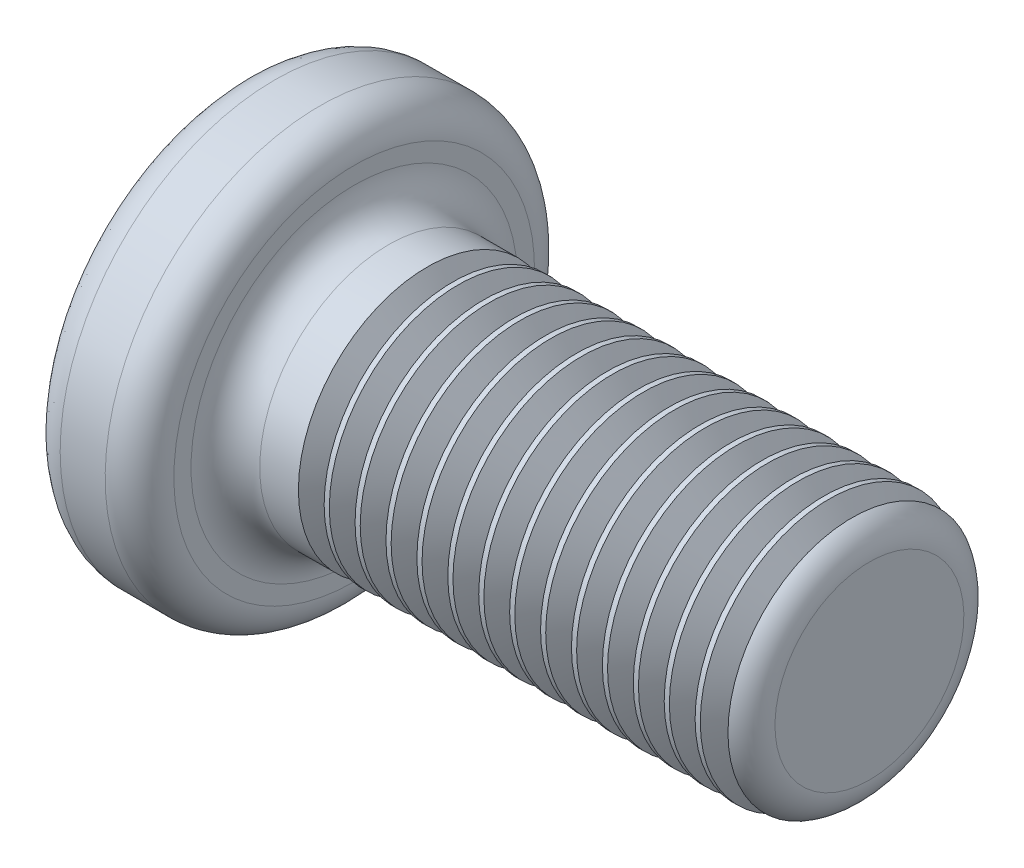
SolidWorks part; units mm, degrees
ref_plane "Front" through (0, 0, 0) normal (0, 0, 1) x (1, 0, 0)
ref_plane "Top" through (0, 0, 0) normal (0, 1, 0) x (1, 0, 0)
ref_plane "Right" through (0, 0, 0) normal (1, 0, 0) x (0, 0, -1)
sketch "Sketch1" plane through (0, 0, 0) normal (0, 0, 1) x (1, 0, 0)
  line L0 (-8.6356, 0) -> (3, 0) construction
  line L1 (8, 0) -> (8, 1.5)
  line L2 (8, 1.5) -> (2, 1.5)
  line L3 (2, 1.5) -> (2, 2.5)
  line L4 (2, 2.5) -> (0.8775, 2.5)
  line L5 (8, 0) -> (0, 0)
  arc A0 (0.8775, 2.5) -> (0, 0) centre (4, 0) ccw
  dimension "rf" = 4
  dimension "st" = 3
  dimension "k" = 2
  dimension "dk" = 5
  dimension "l" = 6
  dimension "a" = 1
revolve "Base" add sketch "Sketch1" angle 360 about L0
cosmetic thread "ThreadCosmetic1" parameters "D1"=5.5, "D2"=2.4
sketch "Sketch2" plane through (0, 0, 0) normal (1, 0, 0) x (0, 0, -1)
  line L0 (6.5369, 0) -> (-7.0008, 0) construction
  line L1 (0, 6.811) -> (0, -6.4314) construction
  line L2 (-0.3, 1.5) -> (0.3, 1.5)
  line L3 (0.3, 1.5) -> (0.3, 0.3)
  line L4 (0.3, 0.3) -> (1.5, 0.3)
  line L5 (1.5, 0.3) -> (1.5, -0.3)
  line L6 (0.3, -0.3) -> (1.5, -0.3)
  line L7 (0.3, -1.5) -> (0.3, -0.3)
  line L8 (-0.3, -1.5) -> (0.3, -1.5)
  line L9 (-0.3, -1.5) -> (-0.3, -0.3)
  line L10 (-0.3, -0.3) -> (-1.5, -0.3)
  line L11 (-1.5, 0.3) -> (-1.5, -0.3)
  line L12 (-0.3, 0.3) -> (-1.5, 0.3)
  line L13 (-0.3, 1.5) -> (-0.3, 0.3)
  point P5 (-1.5, 0)
  point P11 (1.5, 0)
  point P15 (0, -1.5)
  point P20 (0, 1.5)
  dimension "m" = 3
  dimension "D2" = 3
  dimension "D3" = 0.6
  dimension "D4" = 0.6
extrude "Cut-Extrude1" cut sketch "Sketch2" along normal blind 1.2
fillet "Fillet1" radius 0.4 4 edges at (2, -1.5, 0) (8, -1.5, 0) (2, -2.5, 0) (0.8775, -2.5, 0)
draft "Draft1" type of draft neutral plane draft angle 30 neutral plane "Right" faces to draft 4 face at (0.749, 1.5, 0) face at (0.749, 0, 1.5) face at (0.749, -1.5, 0) face at (0.749, 0, -1.5) neutral plane through (0, 0, 0) neutral plane normal (1, 0, 0) reverse direction yes parameters "D1"=30
sketch "Sketch3" plane through (0, 0, 0) normal (0, 0, 1) x (1, 0, 0)
  line L0 (2.85, 1.8) -> (3.15, 1.8)
  line L1 (3.15, 1.8) -> (3.15, 1.5)
  line L2 (3.15, 1.5) -> (3, 1.2402)
  line L3 (3, 1.2402) -> (2.85, 1.5)
  line L4 (2.85, 1.5) -> (2.85, 1.8)
  line L5 (0, 0) -> (33.8691, 0) construction
  line L6 (2, -2.5) -> (2, 2.5) construction
  dimension "D1" = 3
  dimension "D3" = 1
revolve "Cut-Revolve10" cut sketch "Sketch3" angle 360 about L5
pattern_linear "LPattern10" count 14 spacing 0.36 along (1, 0, 0) of "Cut-Revolve10"
equation "\"D3@Sketch2\" = \"m@Sketch2\" / 5"
equation "\"D4@Sketch2\" = \"D3@Sketch2\""
equation "\"D2@Sketch2\" = \"m@Sketch2\""
equation "\"D2@ThreadCosmetic1\" = \"st@Sketch1\"  * 4 / 5"
equation "\"D1@ThreadCosmetic1\" = \"l@Sketch1\" - \"a@Sketch1\""
equation "\"D1@Sketch3\" = \"st@Sketch1\""
equation "\"D2@Sketch3\" = (  \"st@Sketch1\" - \"D2@ThreadCosmetic1\" )  / 2"
equation "\"D3@Sketch3\" = \"a@Sketch1\""
equation "\"D3@LPattern10\" = \"D2@Sketch3\" * 1.2"
equation "\"D1@LPattern10\" = \"D1@ThreadCosmetic1\" / \"D3@LPattern10\""
